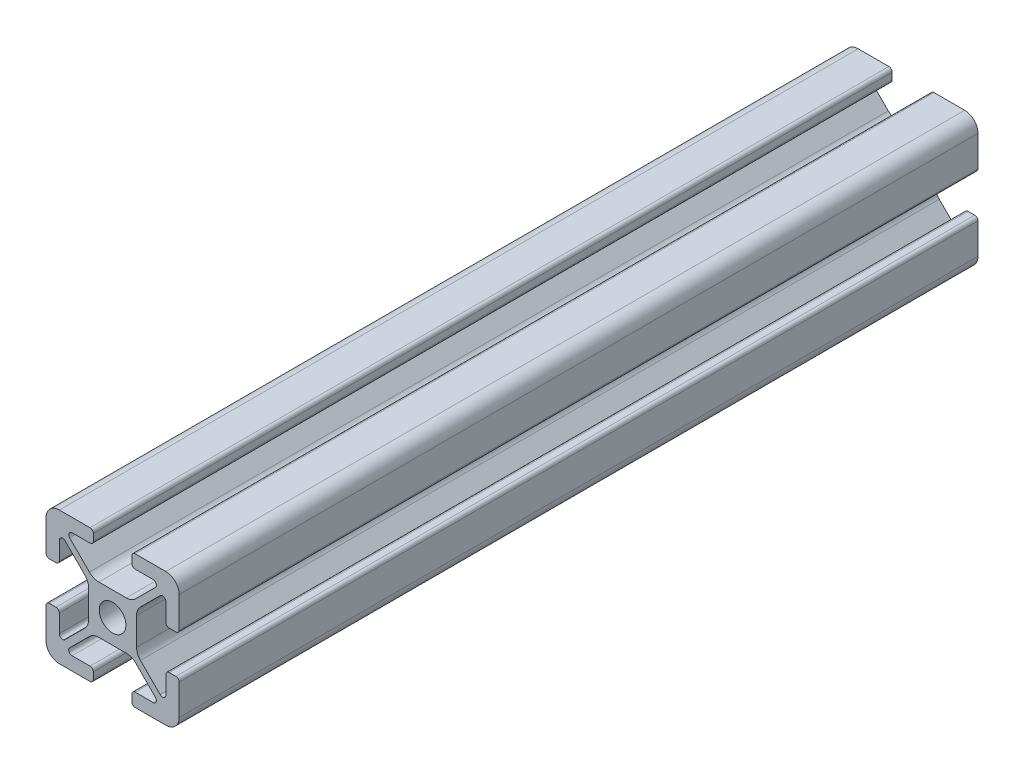
SolidWorks part; units mm, degrees
ref_plane "Front Plane" through (0, 0, 0) normal (0, 0, 1) x (1, 0, 0)
ref_plane "Top Plane" through (0, 0, 0) normal (0, 1, 0) x (1, 0, 0)
ref_plane "Right Plane" through (0, 0, 0) normal (1, 0, 0) x (0, 0, -1)
sketch "Sketch1" plane through (0, 0, 0) normal (0, 0, 1) x (1, 0, 0)
  line L0 (4.4179, 5.3159) -> (8.178, 9.076)
  line L1 (-10.16, -12.7) -> (-4.309, -12.7)
  line L2 (-12.7, -10.16) -> (-12.7, -4.309)
  line L3 (-10.16, 12.7) -> (-4.309, 12.7)
  line L4 (12.7, -10.16) -> (12.7, -4.309)
  line L5 (-12.7, -12.7) -> (12.7, 12.7) construction
  line L6 (-12.7, 12.7) -> (12.7, -12.7) construction
  line L7 (-2.6219, -4.572) -> (2.6219, -4.572)
  line L8 (-4.572, -2.6219) -> (-4.572, 2.6219)
  line L9 (-2.6219, 4.572) -> (2.6219, 4.572)
  line L10 (4.572, -2.6219) -> (4.572, 2.6219)
  line L11 (-4.572, -4.572) -> (4.572, 4.572) construction
  line L12 (-4.572, 4.572) -> (4.572, -4.572) construction
  line L13 (5.3159, 4.4179) -> (9.076, 8.178)
  line L14 (5.3159, -4.4179) -> (9.076, -8.178)
  line L15 (4.4179, -5.3159) -> (8.178, -9.076)
  line L16 (-4.4179, -5.3159) -> (-8.178, -9.076)
  line L17 (-5.3159, -4.4179) -> (-9.076, -8.178)
  line L18 (-5.3159, 4.4179) -> (-9.076, 8.178)
  line L19 (-4.4179, 5.3159) -> (-8.178, 9.076)
  line L20 (-3.674, 4.572) -> (-3.8683, 4.7663) construction
  line L21 (-10.16, 10.16) -> (10.16, 10.16) construction
  line L22 (-7.7289, 10.16) -> (-4.309, 10.16)
  line L23 (10.16, -7.7289) -> (10.16, -4.309)
  line L24 (-7.7289, -10.16) -> (-4.309, -10.16)
  line L25 (-10.16, -7.7289) -> (-10.16, -4.309)
  line L26 (-10.16, -10.16) -> (-10.16, 10.16) construction
  line L27 (-10.16, -10.16) -> (10.16, -10.16) construction
  line L28 (10.16, -10.16) -> (10.16, 10.16) construction
  line L29 (-4.572, 3.674) -> (-17.3082, 3.674) construction
  line L30 (-4.572, -3.674) -> (-17.7261, -3.674) construction
  line L31 (-17.7261, -3.674) -> (20.6347, -3.674) construction
  line L32 (-4.572, 3.674) -> (19.3811, 3.674) construction
  line L33 (-12.7, 4.309) -> (-12.7, 10.16)
  line L34 (-10.16, 4.309) -> (-10.16, 7.7289)
  line L35 (-12.7, -12.7) -> (-12.7, 12.7) construction
  line L36 (12.7, 4.309) -> (12.7, 10.16)
  line L37 (10.16, 4.309) -> (10.16, 7.7289)
  line L38 (12.7, -12.7) -> (12.7, 12.7) construction
  line L39 (-3.674, 10.795) -> (-3.674, 12.065)
  line L40 (3.674, 10.795) -> (3.674, 12.065)
  line L41 (-3.674, -10.795) -> (-3.674, -12.065)
  line L42 (3.674, -10.795) -> (3.674, -12.065)
  line L43 (4.309, -10.16) -> (7.7289, -10.16)
  line L44 (4.309, -12.7) -> (10.16, -12.7)
  line L45 (4.309, 12.7) -> (10.16, 12.7)
  line L46 (-12.7, -12.7) -> (12.7, -12.7) construction
  line L47 (4.309, 10.16) -> (7.7289, 10.16)
  line L48 (-12.7, 12.7) -> (12.7, 12.7) construction
  line L49 (-12.065, 3.674) -> (-10.795, 3.674)
  line L50 (-12.065, -3.674) -> (-10.795, -3.674)
  line L51 (10.795, -3.674) -> (12.065, -3.674)
  line L52 (12.065, 3.674) -> (10.795, 3.674)
  circle A0 centre (0, 0) radius 2.54
  arc A1 (5.3159, -4.4179) -> (4.572, -2.6219) centre (7.112, -2.6219) cw
  arc A2 (5.3159, 4.4179) -> (4.572, 2.6219) centre (7.112, 2.6219) ccw
  arc A3 (4.4179, 5.3159) -> (2.6219, 4.572) centre (2.6219, 7.112) cw
  arc A4 (-4.4179, 5.3159) -> (-2.6219, 4.572) centre (-2.6219, 7.112) ccw
  arc A5 (-5.3159, 4.4179) -> (-4.572, 2.6219) centre (-7.112, 2.6219) cw
  arc A6 (-5.3159, -4.4179) -> (-4.572, -2.6219) centre (-7.112, -2.6219) ccw
  arc A7 (4.4179, -5.3159) -> (2.6219, -4.572) centre (2.6219, -7.112) ccw
  arc A8 (-4.4179, -5.3159) -> (-2.6219, -4.572) centre (-2.6219, -7.112) cw
  arc A9 (-10.16, -12.7) -> (-12.7, -10.16) centre (-10.16, -10.16) cw
  arc A10 (10.16, -12.7) -> (12.7, -10.16) centre (10.16, -10.16) ccw
  arc A11 (10.16, 12.7) -> (12.7, 10.16) centre (10.16, 10.16) cw
  arc A12 (-12.7, 10.16) -> (-10.16, 12.7) centre (-10.16, 10.16) cw
  arc A13 (-7.7289, -10.16) -> (-8.178, -9.076) centre (-7.7289, -9.525) cw
  arc A14 (-10.16, -7.7289) -> (-9.076, -8.178) centre (-9.525, -7.7289) ccw
  arc A15 (10.16, -7.7289) -> (9.076, -8.178) centre (9.525, -7.7289) cw
  arc A16 (8.178, -9.076) -> (7.7289, -10.16) centre (7.7289, -9.525) cw
  arc A17 (9.076, 8.178) -> (10.16, 7.7289) centre (9.525, 7.7289) cw
  arc A18 (8.178, 9.076) -> (7.7289, 10.16) centre (7.7289, 9.525) ccw
  arc A19 (-7.7289, 10.16) -> (-8.178, 9.076) centre (-7.7289, 9.525) ccw
  arc A20 (-9.076, 8.178) -> (-10.16, 7.7289) centre (-9.525, 7.7289) ccw
  arc A21 (-10.16, -4.309) -> (-10.795, -3.674) centre (-10.795, -4.309) ccw
  arc A22 (-12.7, -4.309) -> (-12.065, -3.674) centre (-12.065, -4.309) cw
  arc A23 (-3.674, -12.065) -> (-4.309, -12.7) centre (-4.309, -12.065) cw
  arc A24 (-3.674, -10.795) -> (-4.309, -10.16) centre (-4.309, -10.795) ccw
  arc A25 (3.674, -10.795) -> (4.309, -10.16) centre (4.309, -10.795) cw
  arc A26 (3.674, -12.065) -> (4.309, -12.7) centre (4.309, -12.065) ccw
  arc A27 (10.16, -4.309) -> (10.795, -3.674) centre (10.795, -4.309) cw
  arc A28 (12.7, -4.309) -> (12.065, -3.674) centre (12.065, -4.309) ccw
  arc A29 (10.16, 4.309) -> (10.795, 3.674) centre (10.795, 4.309) ccw
  arc A30 (12.7, 4.309) -> (12.065, 3.674) centre (12.065, 4.309) cw
  arc A31 (4.309, 10.16) -> (3.674, 10.795) centre (4.309, 10.795) cw
  arc A32 (3.674, 12.065) -> (4.309, 12.7) centre (4.309, 12.065) cw
  arc A33 (-4.309, 10.16) -> (-3.674, 10.795) centre (-4.309, 10.795) ccw
  arc A34 (-3.674, 12.065) -> (-4.309, 12.7) centre (-4.309, 12.065) ccw
  arc A35 (-12.7, 4.309) -> (-12.065, 3.674) centre (-12.065, 4.309) ccw
  arc A36 (-10.16, 4.309) -> (-10.795, 3.674) centre (-10.795, 4.309) cw
  point P0 (0, 0)
  point P16 (1.8779, 6.3681)
  point P17 (12.7565, 17.2467)
  point P18 (2.7759, 5.47)
  point P31 (0, 0)
  point P32 (13.6546, 16.3486)
  dimension "D3" = 5.08
  dimension "D8" = 2.54
  dimension "D9" = 0.635
  dimension "D10" = 0.635
  dimension "D1" = 25.4
  dimension "D2" = 25.4
  dimension "D4" = 9.144
  dimension "D5" = 1.27
  dimension "D7" = 2.54
  dimension "D6" = 4
extrude "Boss-Extrude1" add sketch "Sketch1" along normal blind 152.4 contours A36 L34 A20 L18 A5 L8 A6 L17 A14 L25 A21 L50 A22 L2 A9 L1 A23 L41 A24 L24 A13 L16 A8 L7 A7 L15 A16 L43 A25 L42 A26 L44 A10 L4 A28 L51 A27 L23 A15 L14 A1 L10 A2 L13 A17 L37 A29 L52 A30 L36 A11
